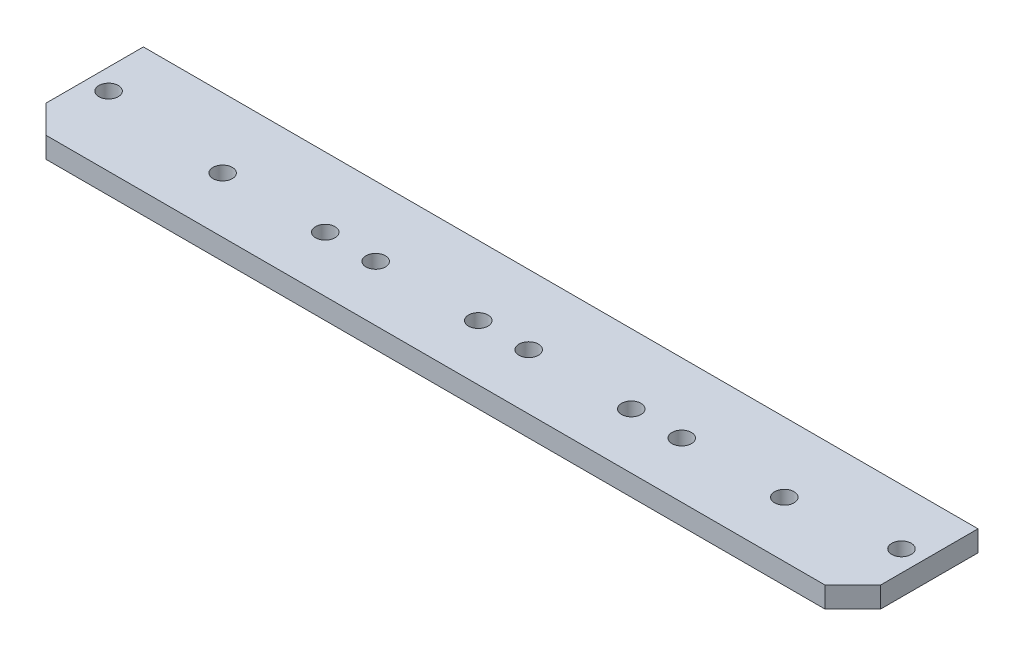
SolidWorks part; units mm, degrees
ref_plane "前视基准面" through (0, 0, 0) normal (0, 0, 1) x (1, 0, 0)
ref_plane "上视基准面" through (0, 0, 0) normal (0, 1, 0) x (1, 0, 0)
ref_plane "右视基准面" through (0, 0, 0) normal (1, 0, 0) x (0, 0, -1)
sketch "草图1" plane through (0, 0, 0) normal (0, 1, 0) x (1, 0, 0)
  line L1 (-60, 17.5) -> (60, 17.5)
  line L2 (-60, 17.5) -> (-60, -17.5)
  line L3 (-60, -17.5) -> (60, -17.5)
  line L4 (60, 17.5) -> (60, -17.5)
  line L5 (-60, 17.5) -> (60, -17.5) construction
  line L6 (-60, -17.5) -> (60, 17.5) construction
  point P0 (0, 0)
  dimension "D1" = 120
  dimension "D2" = 35
extrude "凸台-拉伸1" add sketch "草图1" along normal blind 3
sketch "草图2" plane through (0, 3, 0) normal (0, 1, 0) x (1, 0, 0)
  line L0 (0, 17.5) -> (0, -17.5) construction
  line L1 (60, 17.5) -> (-60, 17.5) construction
  line L2 (-60, -17.5) -> (60, -17.5) construction
  line L3 (15, 17.5) -> (-15, 17.5)
  line L4 (-15, 17.5) -> (-15, 0.5)
  line L5 (-15, 0.5) -> (15, 0.5)
  line L6 (15, 17.5) -> (15, 0.5)
  point P10 (0, 0.5)
  dimension "D1" = 18
  dimension "D2" = 30
extrude "切除-拉伸1" cut sketch "草图2" against normal through all
sketch "草图3" plane through (0, 3, 0) normal (0, 1, 0) x (1, 0, 0)
  line L0 (0, -17.5) -> (0, 15) construction
  line L1 (-60, -17.5) -> (60, -17.5) construction
  line L2 (-57, 12.5) -> (-57, -7.5) construction
  line L3 (-60, 17.5) -> (-60, -17.5) construction
  line L4 (-15, 17.5) -> (-60, 17.5) construction
  circle A0 centre (-57, 12.5) radius 1.4
  circle A1 centre (-57, -7.5) radius 1.4
  circle A2 centre (57, -7.5) radius 1.4
  circle A3 centre (57, 12.5) radius 1.4
  dimension "D1" = 3
  dimension "D2" = 5
  dimension "D3" = 20
  dimension "D4" = 2.8
  dimension "D5" = 2.8
extrude "切除-拉伸2" cut sketch "草图3" against normal through all
sketch "草图4" plane through (0, 3, 0) normal (0, 1, 0) x (1, 0, 0)
  line L0 (0, -17.5) -> (0, 15) construction
  line L1 (-60, -17.5) -> (60, -17.5) construction
  line L2 (-44.7708, -9.5) -> (43.4775, -9.5) construction
  circle A0 centre (5.4, -9.5) radius 1.4
  circle A1 centre (20.15, -9.5) radius 1.4
  circle A2 centre (27.4, -9.5) radius 1.4
  circle A3 centre (42.15, -9.5) radius 1.4
  circle A4 centre (-1.85, -9.5) radius 1.4
  circle A5 centre (-16.6, -9.5) radius 1.4
  circle A6 centre (-23.85, -9.5) radius 1.4
  circle A7 centre (-38.6, -9.5) radius 1.4
  dimension "D2" = 8
  dimension "D3" = 14.75
  dimension "D4" = 14.75
  dimension "D5" = 14.75
  dimension "D6" = 14.75
  dimension "D7" = 2.8
  dimension "D8" = 2.8
  dimension "D9" = 2.8
  dimension "D10" = 2.8
  dimension "D11" = 7.25
  dimension "D13" = 7.25
  dimension "D14" = 7.25
  dimension "D15" = 2.8
  dimension "D12" = 4
extrude "切除-拉伸3" cut sketch "草图4" against normal through all
sketch "草图5" plane through (0, 3, 0) normal (0, 1, 0) x (1, 0, 0)
  line L0 (0, 15.4204) -> (0, -17.5) construction
  line L1 (-60, -17.5) -> (60, -17.5) construction
  line L2 (-15, 17.5) -> (-60, 17.5) construction
  line L3 (-35, 10) -> (-25, 10)
  line L4 (-35, 10) -> (-35, 5)
  line L5 (-35, 5) -> (-25, 5)
  line L6 (-25, 10) -> (-25, 5)
  line L7 (-35, 10) -> (-25, 5) construction
  line L8 (-35, 5) -> (-25, 10) construction
  line L10 (25, 10) -> (25, 5)
  line L11 (35, 5) -> (25, 5)
  line L12 (35, 10) -> (35, 5)
  line L13 (35, 10) -> (25, 10)
  point P4 (-30, 7.5)
  dimension "D1" = 10
  dimension "D2" = 5
  dimension "D3" = 10
  dimension "D4" = 30
extrude "切除-拉伸4" cut sketch "草图5" against normal through all
chamfer "倒角1" distance 4 angle 65 1 edges at (-15, 1.5, -17.5)
chamfer "倒角2" distance 4 angle 65 1 edges at (15, 1.5, -17.5)
fillet "圆角1" radius 5 2 edges at (15, 1.5, -0.5) (-15, 1.5, -0.5)
chamfer "倒角3" distance 4 angle 45 2 edges at (60, 1.5, 17.5) (-60, 1.5, 17.5)
sketch "草图6" plane through (0, 3, 0) normal (0, 1, 0) x (1, 0, 0)
  line L0 (60, -13.5) -> (60, 17.5) construction
  line L1 (-60, 17.5) -> (60, 17.5)
  line L2 (-60, 17.5) -> (-60, 0.5)
  line L3 (-60, 0.5) -> (60, 0.5)
  line L4 (60, 17.5) -> (60, 0.5)
extrude "切除-拉伸5" cut sketch "草图6" against normal through all
